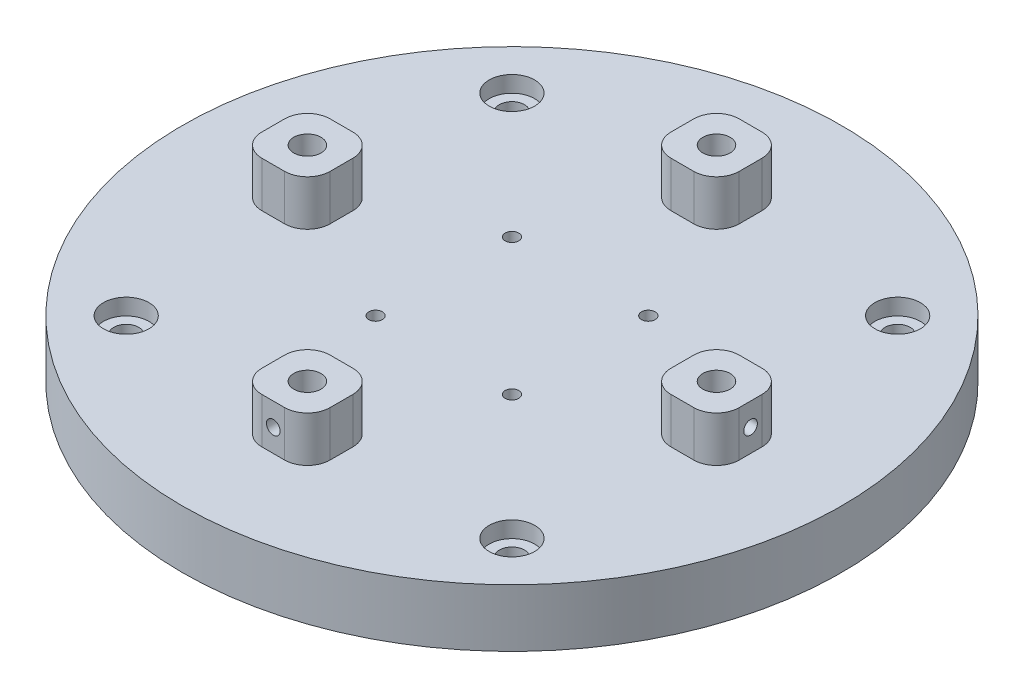
SolidWorks part; units mm, degrees
ref_plane "Front Plane" through (0, 0, 0) normal (0, 0, 1) x (1, 0, 0)
ref_plane "Top Plane" through (0, 0, 0) normal (0, 1, 0) x (1, 0, 0)
ref_plane "Right Plane" through (0, 0, 0) normal (1, 0, 0) x (0, 0, -1)
sketch "Sketch1" plane through (0, 0, 0) normal (0, 1, 0) x (1, 0, 0)
  circle A0 centre (0, 0) radius 72.5
  dimension "D1" = 145
extrude "Boss-Extrude1" add sketch "Sketch1" along normal blind 12.7
hole_wizard "CBORE for M5 Hex Head Bolt2" positions "Sketch6" profile "Sketch7" counterbore size "M5" standard "ANSI Metric" end condition up to next
sketch "Sketch6" plane through (0, 12.7, 0) normal (0, 1, 0) x (1, 0, 0)
  line L0 (0, 0) -> (42.4264, 42.4264) construction
  line L2 (0, 0) -> (0, -50000) construction
  line L3 (0, 0) -> (-42.4264, -42.4264) construction
  point P0 (42.4264, 42.4264)
  point P17 (42.4264, -42.4264)
  point P18 (-42.4264, -42.4264)
  point P19 (-42.4264, 42.4264)
  dimension "D1" = 60
  dimension "D2" = 45
  dimension "D3" = 4
sketch "Sketch7" plane through (42.4264, 12.7, -42.4264) normal (1, 0, 0) x (0, 0, 1)
  line L0 (0, 0) -> (0, 12.7)
  line L1 (0, 12.7) -> (2.75, 12.7)
  line L3 (2.75, 12.7) -> (2.75, 3.58)
  line L4 (2.75, 3.58) -> (5, 3.58)
  line L5 (5, 3.58) -> (5, 0)
  line L7 (5, 0) -> (0, 0)
  line L11 (0, -6.35) -> (0, 107.95) construction
  dimension "Thru Hole Dia." = 5.5
  dimension "Thru Hole Depth" = 12.7
  dimension "C'Bore Dia." = 10
  dimension "C'Bore Depth" = 3.58
sketch "Sketch11" plane through (0, 12.7, 0) normal (0, 1, 0) x (1, 0, 0)
  line L1 (-7.5, -37.5) -> (7.5, -37.5)
  line L2 (-7.5, -37.5) -> (-7.5, -52.5)
  line L3 (-7.5, -52.5) -> (7.5, -52.5)
  line L4 (7.5, -37.5) -> (7.5, -52.5)
  line L5 (-7.5, -37.5) -> (7.5, -52.5) construction
  line L6 (-7.5, -52.5) -> (7.5, -37.5) construction
  circle A0 centre (0, -45) radius 3
  point P0 (0, -45)
  dimension "D3" = 6
  dimension "D1" = 45
  dimension "D2" = 15
extrude "Boss-Extrude2" add sketch "Sketch11" along normal blind 10
fillet "Fillet1" radius 5 4 edges at (7.5, 17.7, 37.5) (-7.5, 17.7, 37.5) (-7.5, 17.7, 52.5) (7.5, 17.7, 52.5)
sketch "Sketch18" plane through (0, 0, 52.5) normal (0, 0, 1) x (1, 0, 0)
  line L0 (-2.5, 22.7) -> (2.5, 22.7) construction
  line L1 (0, 22.7) -> (0, 12.7) construction
  line L2 (-2.5, 12.7) -> (2.5, 12.7) construction
  circle A0 centre (0, 17.7) radius 1.5
  point P8 (0, 0)
  dimension "D1" = 3
extrude "Cut-Extrude4" cut sketch "Sketch18" against normal up to next
pattern_circular "CirPattern2" count 4 over 360 about axis through (0, 0, 0) along (0, 1, 0) of "Boss-Extrude2", "Cut-Extrude4", "Fillet1"
sketch "Sketch19" plane through (0, 0, 0) normal (0, -1, 0) x (1, 0, 0)
  line L0 (0, 72.5) -> (0, -72.5) construction
  line L1 (-72.5, 0) -> (72.5, 0) construction
  circle A0 centre (0, 0) radius 72.5 construction
  circle A1 centre (-15, 15) radius 1.5
  circle A2 centre (15, 15) radius 1.5
  circle A3 centre (15, -15) radius 1.5
  circle A4 centre (-15, -15) radius 1.5
  dimension "D1" = 3
  dimension "D2" = 15
  dimension "D3" = 15
extrude "Cut-Extrude5" cut sketch "Sketch19" against normal through all
sketch "Sketch21" plane through (0, 0, 0) normal (0, -1, 0) x (1, 0, 0)
  line L0 (0, 72.5) -> (0, -72.5) construction
  line L1 (-72.5, 0) -> (72.5, 0) construction
  circle A0 centre (-15, 15) radius 3.5
  circle A1 centre (0, 0) radius 72.5 construction
  circle A2 centre (15, 15) radius 3.5
  circle A3 centre (15, -15) radius 3.5
  circle A4 centre (-15, -15) radius 3.5
  point P10 (72.5, 0)
  point P11 (72.5, 0)
  dimension "D1" = 7
extrude "Cut-Extrude6" cut sketch "Sketch21" against normal blind 3
sketch "Sketch22" plane through (0, 0, 0) normal (0, -1, 0) x (1, 0, 0)
  circle A0 centre (0, 0) radius 15
  dimension "D1" = 30
extrude "Boss-Extrude3" add sketch "Sketch22" along normal blind 15
